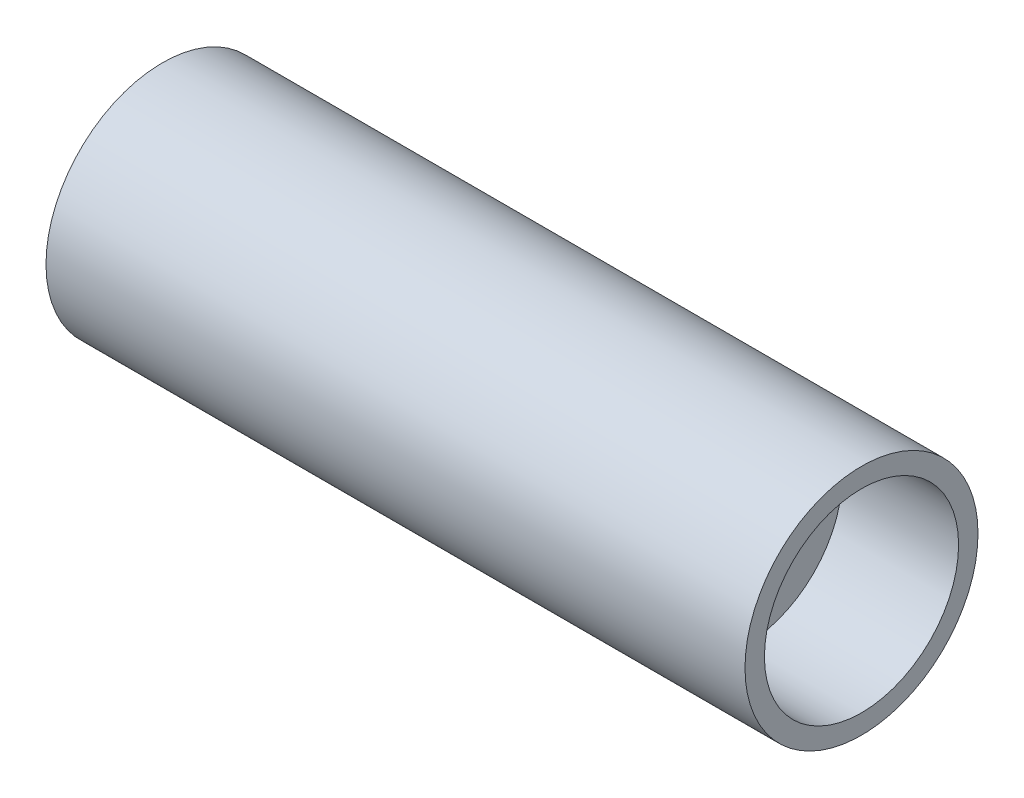
SolidWorks part; units mm, degrees
ref_plane "Front Plane" through (0, 0, 0) normal (0, 0, 1) x (1, 0, 0)
ref_plane "Top Plane" through (0, 0, 0) normal (0, 1, 0) x (1, 0, 0)
ref_plane "Right Plane" through (0, 0, 0) normal (1, 0, 0) x (0, 0, -1)
sketch "Sketch1" plane through (0, 0, 0) normal (1, 0, 0) x (0, 0, -1)
  circle A0 centre (0, 0) radius 3
  dimension "D1" = 6
extrude "Boss-Extrude1" add sketch "Sketch1" along normal blind 8
sketch "Sketch2" plane through (8, 0, 0) normal (1, 0, 0) x (0, 0, -1)
  circle A0 centre (0, 0) radius 2.5
  dimension "D1" = 5
extrude "Cut-Extrude1" cut sketch "Sketch2" against normal blind 3
sketch "Sketch3" plane through (0, 0, 0) normal (-1, 0, 0) x (0, 0, 1)
  circle A0 centre (0, 0) radius 2.5
  dimension "D1" = 5
extrude "Cut-Extrude2" cut sketch "Sketch3" against normal blind 2
sketch "Sketch4" plane through (2, 0, 0) normal (-1, 0, 0) x (0, 0, 1)
  circle A0 centre (0, 0) radius 2.5
extrude "Boss-Extrude2" add sketch "Sketch4" along normal blind 10
sketch "Sketch5" plane through (0, 0, 0) normal (-1, 0, 0) x (0, 0, 1)
  circle A0 centre (0, 0) radius 3
  circle A1 centre (0, 0) radius 2.5
extrude "Boss-Extrude3" add sketch "Sketch5" along normal blind 10
